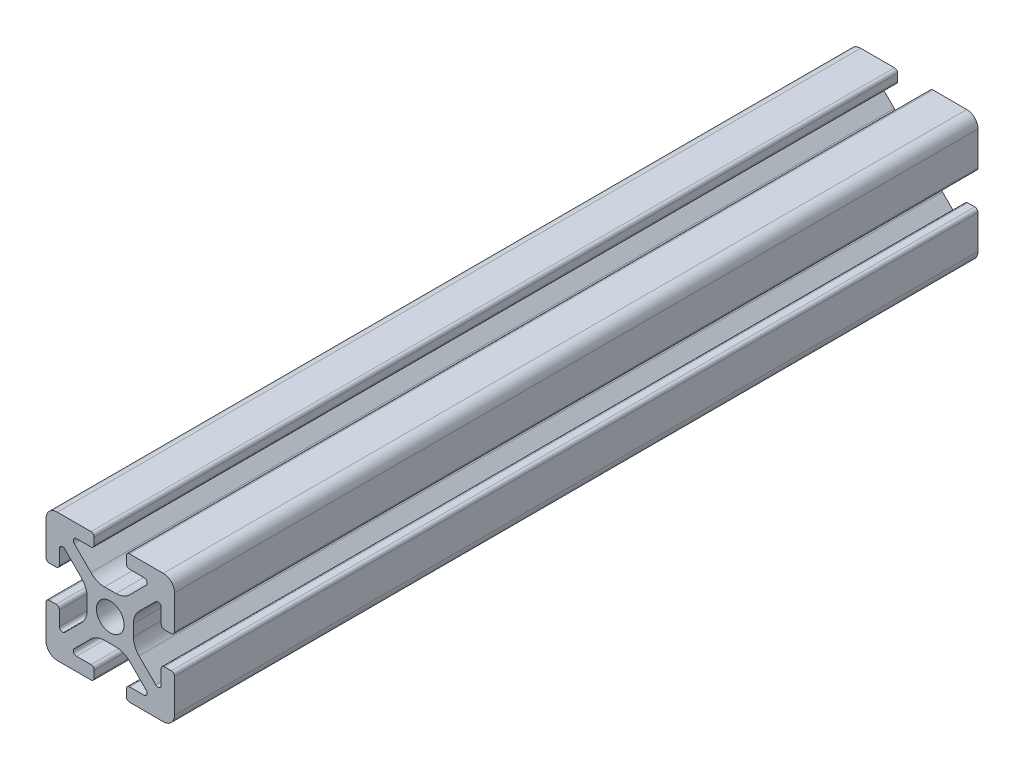
SolidWorks part; units mm, degrees
ref_plane "Front Plane" through (0, 0, 0) normal (0, 0, 1) x (1, 0, 0)
ref_plane "Top Plane" through (0, 0, 0) normal (0, 1, 0) x (1, 0, 0)
ref_plane "Right Plane" through (0, 0, 0) normal (1, 0, 0) x (0, 0, -1)
sketch "Sketch2" plane through (0, 0, 0) normal (0, 0, 1) x (1, 0, 0)
  line L0 (0, 10) -> (0, -10) construction
  line L1 (-10, 0) -> (10, 0) construction
  line L2 (2.5, -10) -> (10, -10)
  line L3 (10, -10) -> (10, -2.5)
  line L4 (2.5, -10) -> (2.5, -7.9246)
  line L5 (2.5, -7.9246) -> (6.4571, -7.9246)
  line L6 (6.4571, -7.9246) -> (2.1325, -3.6)
  line L7 (0, 0) -> (10, -10) construction
  line L8 (10, -2.5) -> (7.9246, -2.5)
  line L9 (7.9246, -2.5) -> (7.9246, -6.4571)
  line L10 (7.9246, -6.4571) -> (3.6, -2.1325)
  line L11 (5.7623, -4.2948) -> (4.2948, -5.7623) construction
  circle A0 centre (0, 0) radius 2.15
  arc A1 (5.25, -7.9246) -> (5.6036, -7.0711) centre (5.25, -7.4246) ccw construction
  point P8 (0, -3.6)
  point P16 (5.0286, -5.0286)
  dimension "Center Hole Diameter" = 4.3
  dimension "D3" = 0.5
  dimension "Rail Height" = 20
  dimension "Rail Width" = 20
  dimension "T-Slot Width" = 5
  dimension "Slot Depth" = 6.4
  dimension "Slot Inner Width" = 11.5
sketch "Sketch3" plane through (0, 0, 0) normal (1, 0, 0) x (0, 0, -1)
  line L0 (-76.2, -10) -> (76.2, -10) construction
  line L1 (-50.8, 0) -> (50.8, 0) construction
  line L2 (0, 10) -> (0, -10) construction
  line L3 (0, 10) -> (0, -10) construction
  point P6 (-50.8, 0)
  point P8 (50.8, 0)
  dimension "D1" = 25.4
  dimension "Length" = 152.4
sketch "Sketch4" plane through (0, 0, 0) normal (0, 0, 1) x (1, 0, 0)
  line L0 (3, -10) -> (8.25, -10)
  line L1 (2.5, -10) -> (10, -10) construction
  line L2 (2.5, -10) -> (2.5, -7.9246) construction
  line L3 (2.5, -7.9246) -> (6.4571, -7.9246) construction
  line L4 (2.5, -8.4246) -> (2.5, -9.5)
  line L5 (3, -7.9246) -> (5.25, -7.9246)
  line L6 (0, -3.6) -> (0.8898, -3.6)
  line L7 (6.4571, -7.9246) -> (2.1325, -3.6) construction
  line L8 (3.0112, -4.4787) -> (5.6036, -7.0711)
  line L9 (10, -10) -> (10, -2.5) construction
  line L10 (7.9246, -6.4571) -> (3.6, -2.1325) construction
  line L11 (7.9246, -2.5) -> (7.9246, -6.4571) construction
  line L12 (7.9246, -5.25) -> (7.9246, -3)
  line L13 (10, -2.5) -> (7.9246, -2.5) construction
  line L14 (8.4246, -2.5) -> (9.5, -2.5)
  line L15 (10, -3) -> (10, -8.25)
  line L16 (7.0711, -5.6036) -> (4.4787, -3.0112)
  line L17 (3.6, 0) -> (3.6, -0.8898)
  line L18 (-10, 0) -> (10, 0) construction
  line L19 (0, -3.6) -> (0, -2.15)
  line L20 (0, 10) -> (0, -10) construction
  line L21 (3.6, 0) -> (2.15, 0)
  arc A0 (2.5, -9.5) -> (3, -10) centre (3, -9.5) ccw
  arc A1 (5.25, -7.9246) -> (5.6036, -7.0711) centre (5.25, -7.4246) ccw construction
  arc A2 (2.5, -8.4246) -> (3, -7.9246) centre (3, -8.4246) cw
  arc A3 (5.25, -7.9246) -> (5.6036, -7.0711) centre (5.25, -7.4246) ccw
  arc A4 (0.8898, -3.6) -> (3.0112, -4.4787) centre (0.8898, -6.6) cw
  arc A5 (8.25, -10) -> (10, -8.25) centre (8.25, -8.25) ccw
  arc A6 (7.0711, -5.6036) -> (7.9246, -5.25) centre (7.4246, -5.25) ccw
  arc A7 (7.9246, -3) -> (8.4246, -2.5) centre (8.4246, -3) cw
  arc A8 (9.5, -2.5) -> (10, -3) centre (9.5, -3) cw
  arc A9 (4.4787, -3.0112) -> (3.6, -0.8898) centre (6.6, -0.8898) cw
  circle A10 centre (0, 0) radius 2.15 construction
  arc A11 (0, -2.15) -> (2.15, 0) centre (0, 0) ccw
  dimension "D1" = 1.75
  dimension "D2" = 3
extrude "Boss-Extrude1" add sketch "Sketch4" along normal mid plane 125
mirror "Mirror1" about plane through (0, 0, 0) normal (1, 0, 0) of bodies 134
mirror "Mirror2" about plane through (0, 0, 0) normal (0, 1, 0) of bodies 135
equation "\"D3@Sketch2\"=\"T-Slot Width@Sketch2\"*0.1"
equation "\"D1@Sketch4\"=\"D3@Sketch2\"*3.5"
equation "\"D2@Sketch4\"=\"D3@Sketch2\"*6"
equation "\"D1@Boss-Extrude1\"=110"
